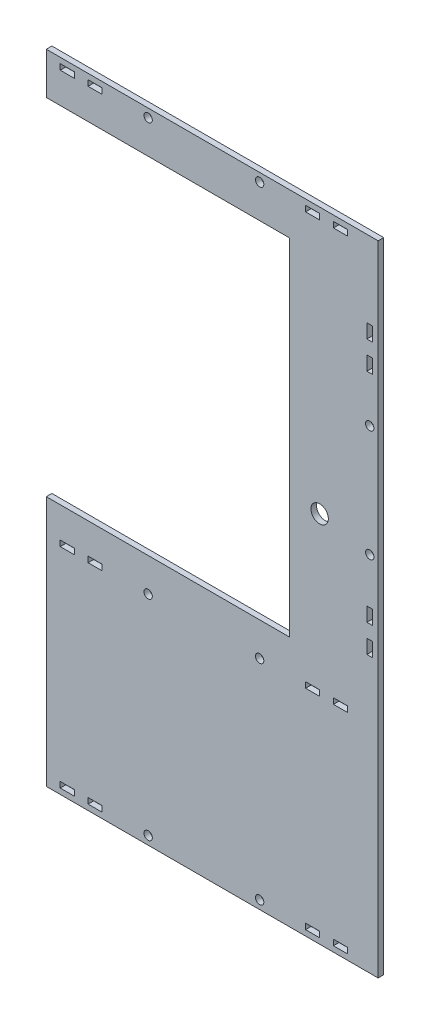
SolidWorks part; units mm, degrees
ref_plane "前视基准面" through (0, 0, 0) normal (0, 0, 1) x (1, 0, 0)
ref_plane "上视基准面" through (0, 0, 0) normal (0, 1, 0) x (1, 0, 0)
ref_plane "右视基准面" through (0, 0, 0) normal (1, 0, 0) x (0, 0, -1)
sketch "草图1" plane through (0, 0, 0) normal (0, 0, 1) x (1, 0, 0)
  line L0 (-46.0613, -2.3972) -> (-51.1113, -0.3472) construction
  line L5 (36.8887, -0.3472) -> (41.9387, -0.3472)
  line L6 (36.8887, -0.3472) -> (36.8887, -2.3972)
  line L11 (36.8887, -2.3972) -> (41.9387, -2.3972)
  line L12 (41.9387, -0.3472) -> (41.9387, -2.3972)
  line L13 (36.8887, -0.3472) -> (41.9387, -2.3972) construction
  line L14 (36.8887, -2.3972) -> (41.9387, -0.3472) construction
  line L15 (46.8887, -0.3472) -> (51.9387, -0.3472)
  line L25 (46.8887, -0.3472) -> (46.8887, -2.3972)
  line L30 (46.8887, -2.3972) -> (51.9387, -2.3972)
  line L31 (51.9387, -0.3472) -> (51.9387, -2.3972)
  line L36 (46.8887, -0.3472) -> (51.9387, -2.3972) construction
  line L37 (46.8887, -2.3972) -> (51.9387, -0.3472) construction
  line L38 (-46.0613, -0.3472) -> (-51.1113, -2.3972) construction
  line L39 (-36.0613, -2.3972) -> (-41.1113, -0.3472) construction
  line L40 (-36.0613, -0.3472) -> (-41.1113, -2.3972) construction
  line L55 (-51.1113, -0.3472) -> (-51.1113, -2.3972)
  line L60 (-46.0613, -2.3972) -> (-51.1113, -2.3972)
  line L61 (-46.0613, -0.3472) -> (-46.0613, -2.3972)
  line L66 (-46.0613, -0.3472) -> (-51.1113, -0.3472)
  line L67 (-41.1113, -0.3472) -> (-41.1113, -2.3972)
  line L68 (-36.0613, -2.3972) -> (-41.1113, -2.3972)
  line L69 (-36.0613, -0.3472) -> (-36.0613, -2.3972)
  line L70 (-36.0613, -0.3472) -> (-41.1113, -0.3472)
  line L81 (-48.5863, -1.3722) -> (49.4137, -1.3722) construction
  line L82 (-19.5863, -149.3722) -> (-8.6103, -149.3722) construction
  line L83 (-46.0613, -150.3972) -> (-51.1113, -148.3472) construction
  line L84 (36.8887, -148.3472) -> (41.9387, -148.3472)
  line L85 (36.8887, -148.3472) -> (36.8887, -150.3972)
  line L86 (36.8887, -150.3972) -> (41.9387, -150.3972)
  line L87 (41.9387, -148.3472) -> (41.9387, -150.3972)
  line L88 (36.8887, -148.3472) -> (41.9387, -150.3972) construction
  line L89 (36.8887, -150.3972) -> (41.9387, -148.3472) construction
  line L90 (46.8887, -148.3472) -> (51.9387, -148.3472)
  line L91 (46.8887, -148.3472) -> (46.8887, -150.3972)
  line L92 (46.8887, -150.3972) -> (51.9387, -150.3972)
  line L93 (51.9387, -148.3472) -> (51.9387, -150.3972)
  line L94 (46.8887, -148.3472) -> (51.9387, -150.3972) construction
  line L95 (46.8887, -150.3972) -> (51.9387, -148.3472) construction
  line L96 (-46.0613, -148.3472) -> (-51.1113, -150.3972) construction
  line L97 (-36.0613, -150.3972) -> (-41.1113, -148.3472) construction
  line L98 (-36.0613, -148.3472) -> (-41.1113, -150.3972) construction
  line L99 (-51.1113, -148.3472) -> (-51.1113, -150.3972)
  line L100 (-46.0613, -150.3972) -> (-51.1113, -150.3972)
  line L101 (-46.0613, -148.3472) -> (-46.0613, -150.3972)
  line L102 (-46.0613, -148.3472) -> (-51.1113, -148.3472)
  line L103 (-41.1113, -148.3472) -> (-41.1113, -150.3972)
  line L104 (-36.0613, -150.3972) -> (-41.1113, -150.3972)
  line L105 (-36.0613, -148.3472) -> (-36.0613, -150.3972)
  line L106 (-36.0613, -148.3472) -> (-41.1113, -148.3472)
  line L107 (59.9198, -57.3722) -> (59.9198, -97.3722) construction
  line L108 (-56.1113, -13.3722) -> (31.071, -13.3722)
  line L109 (-56.1113, 1.6278) -> (62.9198, 1.6278)
  line L110 (-56.1113, 1.6278) -> (-56.1113, -152.3722) construction
  line L111 (-56.1113, -152.3722) -> (62.9198, -152.3722) construction
  line L112 (62.9198, 1.6278) -> (62.9198, -152.3722)
  line L113 (60.9448, -123.8472) -> (58.8948, -128.8972) construction
  line L114 (58.8948, -40.8972) -> (58.8948, -35.8472)
  line L115 (58.8948, -40.8972) -> (60.9448, -40.8972)
  line L116 (60.9448, -40.8972) -> (60.9448, -35.8472)
  line L117 (58.8948, -35.8472) -> (60.9448, -35.8472)
  line L118 (58.8948, -40.8972) -> (60.9448, -35.8472) construction
  line L119 (60.9448, -40.8972) -> (58.8948, -35.8472) construction
  line L120 (58.8948, -30.8972) -> (58.8948, -25.8472)
  line L121 (58.8948, -30.8972) -> (60.9448, -30.8972)
  line L122 (60.9448, -30.8972) -> (60.9448, -25.8472)
  line L123 (58.8948, -25.8472) -> (60.9448, -25.8472)
  line L124 (58.8948, -30.8972) -> (60.9448, -25.8472) construction
  line L125 (60.9448, -30.8972) -> (58.8948, -25.8472) construction
  line L126 (58.8948, -123.8472) -> (60.9448, -128.8972) construction
  line L127 (60.9448, -113.8472) -> (58.8948, -118.8972) construction
  line L128 (58.8948, -113.8472) -> (60.9448, -118.8972) construction
  line L129 (58.8948, -128.8972) -> (60.9448, -128.8972)
  line L130 (60.9448, -123.8472) -> (60.9448, -128.8972)
  line L131 (58.8948, -123.8472) -> (60.9448, -123.8472)
  line L132 (58.8948, -123.8472) -> (58.8948, -128.8972)
  line L133 (58.8948, -118.8972) -> (60.9448, -118.8972)
  line L134 (60.9448, -113.8472) -> (60.9448, -118.8972)
  line L135 (58.8948, -113.8472) -> (60.9448, -113.8472)
  line L136 (58.8948, -113.8472) -> (58.8948, -118.8972)
  line L137 (31.071, -13.3722) -> (31.071, -137.3722)
  line L138 (31.071, -137.3722) -> (-56.1113, -137.3722)
  line L139 (-56.1113, -137.3722) -> (-56.1113, -152.3722)
  line L140 (-56.1113, -13.3722) -> (-56.1113, 1.6278)
  line L141 (20.4137, -149.3722) -> (20.4137, -224.3722) construction
  line L143 (-46.0613, -225.3972) -> (-51.1113, -223.3472) construction
  line L144 (36.8887, -223.3472) -> (41.9387, -223.3472)
  line L145 (36.8887, -223.3472) -> (36.8887, -225.3972)
  line L146 (36.8887, -225.3972) -> (41.9387, -225.3972)
  line L147 (41.9387, -223.3472) -> (41.9387, -225.3972)
  line L148 (36.8887, -223.3472) -> (41.9387, -225.3972) construction
  line L149 (36.8887, -225.3972) -> (41.9387, -223.3472) construction
  line L150 (46.8887, -223.3472) -> (51.9387, -223.3472)
  line L151 (46.8887, -223.3472) -> (46.8887, -225.3972)
  line L152 (46.8887, -225.3972) -> (51.9387, -225.3972)
  line L153 (51.9387, -223.3472) -> (51.9387, -225.3972)
  line L154 (46.8887, -223.3472) -> (51.9387, -225.3972) construction
  line L155 (46.8887, -225.3972) -> (51.9387, -223.3472) construction
  line L156 (-46.0613, -223.3472) -> (-51.1113, -225.3972) construction
  line L157 (-36.0613, -225.3972) -> (-41.1113, -223.3472) construction
  line L158 (-36.0613, -223.3472) -> (-41.1113, -225.3972) construction
  line L159 (-51.1113, -223.3472) -> (-51.1113, -225.3972)
  line L160 (-46.0613, -225.3972) -> (-51.1113, -225.3972)
  line L161 (-46.0613, -223.3472) -> (-46.0613, -225.3972)
  line L162 (-46.0613, -223.3472) -> (-51.1113, -223.3472)
  line L163 (-41.1113, -223.3472) -> (-41.1113, -225.3972)
  line L164 (-36.0613, -225.3972) -> (-41.1113, -225.3972)
  line L165 (-36.0613, -223.3472) -> (-36.0613, -225.3972)
  line L166 (-36.0613, -223.3472) -> (-41.1113, -223.3472)
  line L167 (-56.1113, -152.3722) -> (-56.1113, -227.3972)
  line L168 (-56.1113, -227.3972) -> (62.9198, -227.3972)
  line L169 (62.9198, -227.3972) -> (62.9198, -152.3722)
  circle A6 centre (-19.5863, -1.3722) radius 1.5
  circle A7 centre (20.4137, -1.3722) radius 1.5
  circle A9 centre (-19.5863, -149.3722) radius 1.5
  circle A10 centre (20.4137, -149.3722) radius 1.5
  circle A11 centre (59.9198, -97.3722) radius 1.5
  circle A12 centre (59.9198, -57.3722) radius 1.5
  circle A13 centre (41.9387, -93.6781) radius 3.1213
  circle A14 centre (-19.5863, -224.3722) radius 1.5
  circle A15 centre (20.4137, -224.3722) radius 1.5
  point P8 (-38.5863, -1.3722)
  point P13 (39.4137, -1.3722)
  point P35 (-38.5863, -149.3722)
  point P40 (39.4137, -149.3722)
  point P54 (3.4042, -152.3722)
  point P80 (101.1063, -340.4435)
  point P91 (-38.5863, -224.3722)
  point P96 (39.4137, -224.3722)
  dimension "D1" = 148
  dimension "D2" = 3
  dimension "D4" = 3
  dimension "D5" = 5
  dimension "D6" = 15
  dimension "D7" = 15
extrude "凸台-拉伸1" add sketch "草图1" along normal blind 2
